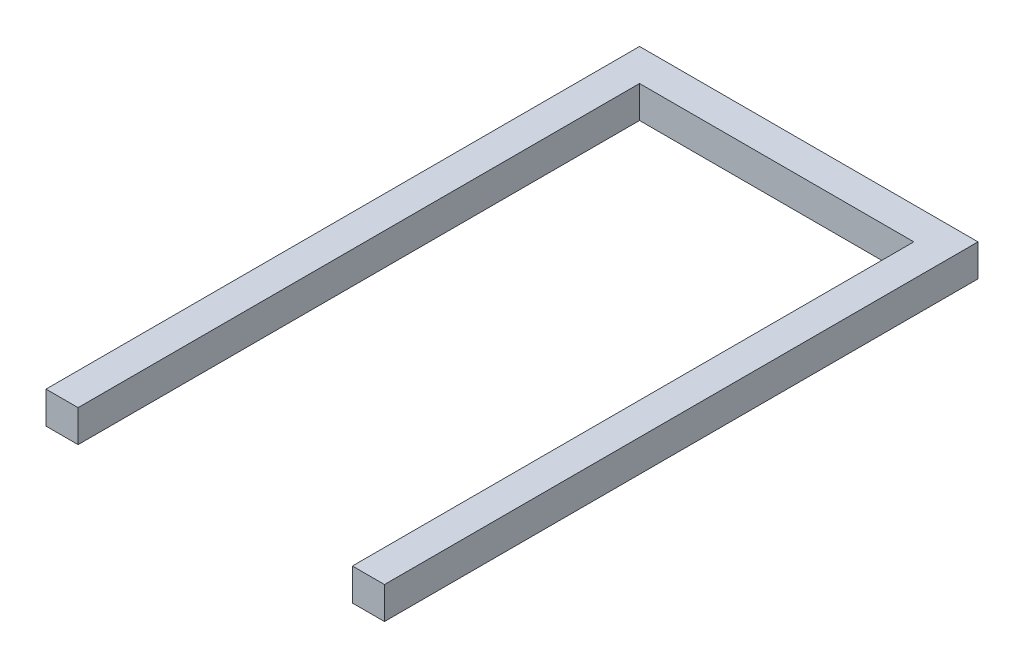
SolidWorks part; units mm, degrees
ref_plane "Front Plane" through (0, 0, 0) normal (0, 0, 1) x (1, 0, 0)
ref_plane "Top Plane" through (0, 0, 0) normal (0, 1, 0) x (1, 0, 0)
ref_plane "Right Plane" through (0, 0, 0) normal (1, 0, 0) x (0, 0, -1)
sketch "Sketch1" plane through (0, 0, 0) normal (0, 1, 0) x (1, 0, 0)
  line L0 (-51.1814, -26.7689) -> (-51.1814, 47.2311)
  line L1 (-51.1814, 47.2311) -> (-8.9814, 47.2311)
  line L2 (-8.9814, 47.2311) -> (-8.9814, -26.7689)
  line L3 (-8.9814, -26.7689) -> (-12.9814, -26.7689)
  line L4 (-12.9814, -26.7689) -> (-12.9814, 43.2311)
  line L5 (-12.9814, 43.2311) -> (-47.1814, 43.2311)
  line L6 (-47.1814, 43.2311) -> (-47.1814, -26.7689)
  line L7 (-47.1814, -26.7689) -> (-51.1814, -26.7689)
  dimension "D1" = 74
  dimension "D2" = 34.2
  dimension "D3" = 4
  dimension "D4" = 4
  dimension "D5" = 4
extrude "Boss-Extrude1" add sketch "Sketch1" along normal blind 4
